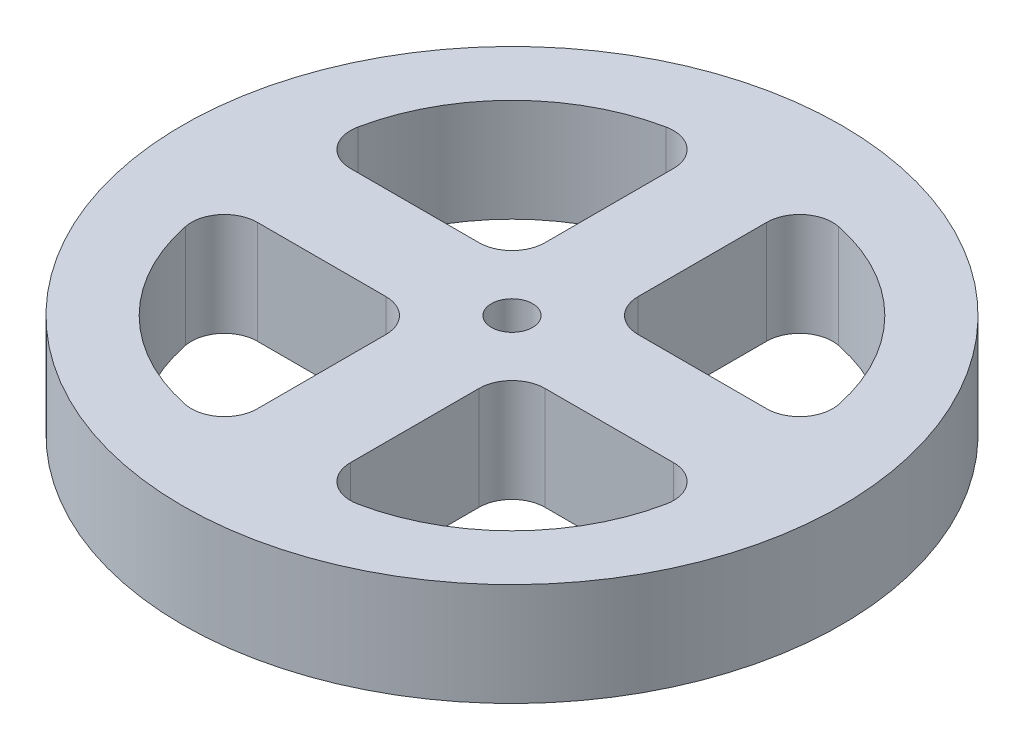
SolidWorks part; units mm, degrees
ref_plane "Front Plane" through (0, 0, 0) normal (0, 0, 1) x (1, 0, 0)
ref_plane "Top Plane" through (0, 0, 0) normal (0, 1, 0) x (1, 0, 0)
ref_plane "Right Plane" through (0, 0, 0) normal (1, 0, 0) x (0, 0, -1)
sketch "Sketch1" plane through (0, 0, 0) normal (0, 1, 0) x (1, 0, 0)
  circle A0 centre (0, 0) radius 0.3175
  circle A1 centre (0, 0) radius 5.08
  dimension "D1" = 0.635
  dimension "D2" = 10.16
extrude "Boss-Extrude1" add sketch "Sketch1" along normal blind 1.5875
sketch "Sketch2" plane through (0, 1.5875, 0) normal (0, 1, 0) x (1, 0, 0)
  line L0 (-0.7184, 0.7184) -> (-0.7184, 3.7664)
  line L1 (-0.7184, 0.7184) -> (-3.7664, 0.7184)
  line L2 (0, 0) -> (-0.7184, 0.7184) construction
  line L3 (-2.8737, 2.8737) -> (-3.5921, 3.5921) construction
  line L4 (0, 5.08) -> (0, -5.08) construction
  line L5 (5.08, 0) -> (-5.08, 0) construction
  line L6 (0.7184, 0.7184) -> (3.7664, 0.7184)
  line L7 (0.7184, 0.7184) -> (0.7184, 3.7664)
  line L8 (0.7184, -0.7184) -> (3.7664, -0.7184)
  line L9 (0.7184, -0.7184) -> (0.7184, -3.7664)
  line L10 (-0.7184, -0.7184) -> (-0.7184, -3.7664)
  line L11 (-0.7184, -0.7184) -> (-3.7664, -0.7184)
  arc A0 (-3.7664, 0.7184) -> (-0.7184, 3.7664) centre (-0.7184, 0.7184) cw
  circle A1 centre (0, 0) radius 5.08 construction
  arc A2 (3.7664, 0.7184) -> (0.7184, 3.7664) centre (0.7184, 0.7184) ccw
  arc A3 (3.7664, -0.7184) -> (0.7184, -3.7664) centre (0.7184, -0.7184) cw
  arc A4 (-3.7664, -0.7184) -> (-0.7184, -3.7664) centre (-0.7184, -0.7184) ccw
  dimension "D1" = 1.016
  dimension "D2" = 1.016
extrude "Cut-Extrude1" cut sketch "Sketch2" against normal through all
fillet "Fillet1" radius 0.508 4 edges at (-0.7184, 0.7937, 0.7184) (0.7184, 0.7937, 0.7184) (0.7184, 0.7937, -0.7184) (-0.7184, 0.7937, -0.7184)
fillet "Fillet2" radius 0.508 8 edges at (-3.7664, 0.7937, 0.7184) (-0.7184, 0.7937, 3.7664) (0.7184, 0.7937, 3.7664) (3.7664, 0.7937, -0.7184) (3.7664, 0.7937, 0.7184) (0.7184, 0.7937, -3.7664) (-3.7664, 0.7937, -0.7184) (-0.7184, 0.7937, -3.7664)
